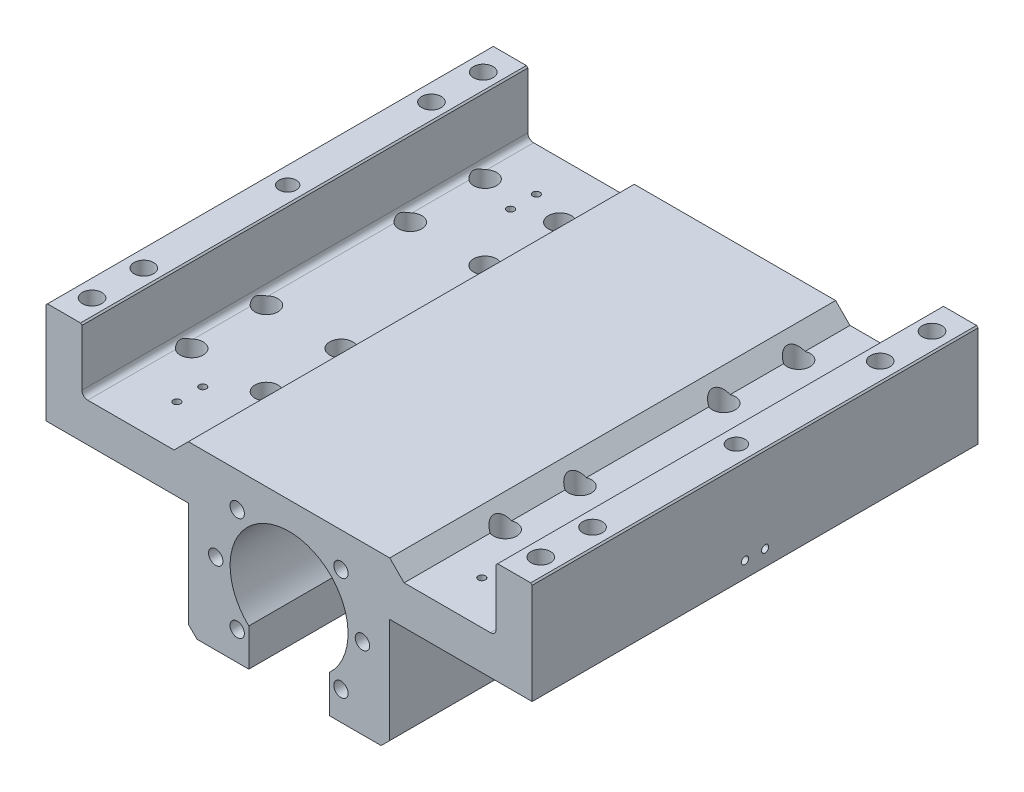
SolidWorks part; units mm, degrees
ref_plane "前视基准面" through (0, 0, 0) normal (0, 0, 1) x (1, 0, 0)
ref_plane "上视基准面" through (0, 0, 0) normal (0, 1, 0) x (1, 0, 0)
ref_plane "右视基准面" through (0, 0, 0) normal (1, 0, 0) x (0, 0, -1)
sketch "草图1" plane through (0, 0, 0) normal (0, 0, 1) x (1, 0, 0)
  line L0 (410.7552, 671.7438) -> (410.2552, 671.2438)
  line L1 (410.2552, 671.2438) -> (410.2552, 636.2438)
  line L2 (422.7552, 651.7438) -> (422.7552, 671.2438)
  line L3 (459.7552, 599.7438) -> (462.7552, 596.7438)
  line L4 (459.7552, 654.7438) -> (454.7552, 649.7438)
  line L5 (526.7552, 596.7438) -> (508.7552, 596.7438)
  line L6 (480.7552, 596.7438) -> (462.7552, 596.7438)
  line L7 (459.7552, 599.7438) -> (459.7552, 636.2438)
  line L8 (422.7552, 671.2438) -> (422.2552, 671.7438)
  line L9 (480.7552, 596.7438) -> (480.7552, 612.6506)
  line L10 (410.2552, 636.2438) -> (459.7552, 636.2438)
  line L11 (529.7552, 636.2438) -> (579.2552, 636.2438)
  line L12 (564.7552, 649.7438) -> (534.7552, 649.7438)
  line L13 (454.7552, 649.7438) -> (424.7552, 649.7438)
  line L14 (567.2552, 671.7438) -> (566.7552, 671.2438)
  line L15 (459.7552, 654.7438) -> (529.7552, 654.7438)
  line L16 (529.7552, 636.2438) -> (529.7552, 599.7438)
  line L17 (578.7552, 671.7438) -> (567.2552, 671.7438)
  line L18 (422.2552, 671.7438) -> (410.7552, 671.7438)
  line L19 (534.7552, 649.7438) -> (529.7552, 654.7438)
  line L20 (526.7552, 596.7438) -> (529.7552, 599.7438)
  line L21 (566.7552, 671.2438) -> (566.7552, 651.7438)
  line L22 (579.2552, 636.2438) -> (579.2552, 671.2438)
  line L23 (579.2552, 671.2438) -> (578.7552, 671.7438)
  line L24 (508.7552, 596.7438) -> (508.7552, 612.6506)
  arc A0 (422.7552, 651.7438) -> (424.7552, 649.7438) centre (424.7552, 651.7438) ccw
  arc A1 (564.7552, 649.7438) -> (566.7552, 651.7438) centre (564.7552, 651.7438) ccw
  arc A2 (508.7552, 612.6506) -> (480.7552, 612.6506) centre (494.7552, 624.744) ccw
extrude "凸台-拉伸1" add sketch "草图1" along normal blind 155
sketch "草图2" plane through (0, 0, 155) normal (0, 0, 1) x (1, 0, 0)
  circle A0 centre (494.7552, 624.744) radius 20.5
  dimension "D1" = 41
extrude "切除-拉伸1" cut sketch "草图2" against normal blind 100
sketch "草图3" plane through (0, 0, 155) normal (0, 0, 1) x (1, 0, 0)
  line L0 (494.7552, 624.744) -> (494.7552, 663.4123) construction
  line L1 (494.7552, 624.744) -> (440.7565, 624.744) construction
  line L3 (494.7552, 624.744) -> (464.9696, 654.5296) construction
  line L4 (494.7552, 624.744) -> (527.5427, 657.5315) construction
  circle A0 centre (494.7552, 624.744) radius 25.5 construction
  dimension "D3" = 51
  dimension "D1" = 45
  dimension "D2" = 45
hole_wizard "M6 螺纹孔1" positions "3D草图1" profile "草图4" tap size "M6" standard "Gb"
sketch3d "3D草图1"
  line L0 (494.7552, 624.744, 155) -> (464.9696, 654.5296, 155) construction
  line L1 (494.7552, 624.744, 155) -> (440.7565, 624.744, 155) construction
  line L2 (494.7552, 624.744, 155) -> (527.5427, 657.5315, 155) construction
  circle A0 centre (494.7552, 624.744, 155) radius 25.5 construction
  point P0 (476.724, 642.7752, 155)
  point P6 (494.7552, 624.744, 180.5)
  point P7 (469.2552, 624.744, 155)
  point P11 (476.724, 606.7128, 155)
  point P15 (512.7864, 606.7128, 155)
  point P17 (520.2552, 624.744, 155)
  point P19 (512.7864, 642.7752, 155)
sketch "草图4" plane through (476.724, 642.7752, 155) normal (1, 0, 0) x (0, -1, 0)
  line L0 (0, 0) -> (0, 21.5022)
  line L1 (0, 21.5022) -> (2.5, 20)
  line L2 (2.5, 20) -> (2.5, 0)
  line L5 (2.5, 0) -> (0, 0)
  line L10 (0, 21.5022) -> (-2.5, 20) construction
  line L11 (0, -6.35) -> (0, 107.95) construction
  dimension "螺纹孔钻头直径" = 5
  dimension "螺纹孔钻头深度" = 20
  dimension "导头角度" = 118
cosmetic thread "孔螺蚊线1" parameters "D1"=12, "D2"=6
cosmetic thread "孔螺蚊线2" parameters "D1"=12, "D2"=6
cosmetic thread "孔螺蚊线3" parameters "D1"=12, "D2"=6
cosmetic thread "孔螺蚊线4" parameters "D1"=12, "D2"=6
cosmetic thread "孔螺蚊线5" parameters "D1"=12, "D2"=6
cosmetic thread "孔螺蚊线6" parameters "D1"=12, "D2"=6
hole_wizard "M3 螺纹孔1" positions "草图6" profile "草图5" tap size "M3" standard "Gb"
sketch "草图6" plane through (410.2552, 0, 0) normal (-1, 0, 0) x (0, 0, 1)
  line L0 (0, 671.2438) -> (0, 636.2438) construction
  line L1 (155, 671.7438) -> (0, 671.7438) construction
  point P0 (74, 641.7438)
  point P2 (81, 641.7438)
  dimension "D1" = 7
  dimension "D2" = 74
  dimension "D3" = 30
sketch "草图5" plane through (410.2552, 641.7438, 74) normal (0, 1, 0) x (0, 0, 1)
  line L0 (0, 0) -> (0, 4.7511)
  line L1 (0, 4.7511) -> (1.25, 4)
  line L2 (1.25, 4) -> (1.25, 0)
  line L5 (1.25, 0) -> (0, 0)
  line L10 (0, 4.7511) -> (-1.25, 4) construction
  line L11 (0, -6.35) -> (0, 107.95) construction
  dimension "螺纹孔钻头直径" = 2.5
  dimension "螺纹孔钻头深度" = 4
  dimension "导头角度" = 118
cosmetic thread "孔螺蚊线7" parameters "D1"=4, "D2"=3
cosmetic thread "孔螺蚊线8" parameters "D1"=4, "D2"=3
hole_wizard "M3 螺纹孔2" positions "草图8" profile "草图7" tap size "M3" standard "Gb"
sketch "草图8" plane through (579.2552, 0, 0) normal (1, 0, 0) x (0, 0, -1)
  line L0 (0, 636.2438) -> (0, 671.2438) construction
  line L1 (-155, 671.7438) -> (0, 671.7438) construction
  point P0 (-74, 641.7438)
  point P2 (-81, 641.7438)
  dimension "D1" = 7
  dimension "D2" = 74
  dimension "D3" = 30
sketch "草图7" plane through (579.2552, 641.7438, 74) normal (0, 1, 0) x (0, 0, -1)
  line L0 (0, 0) -> (0, 8.2511)
  line L1 (0, 8.2511) -> (1.25, 7.5)
  line L2 (1.25, 7.5) -> (1.25, 0)
  line L5 (1.25, 0) -> (0, 0)
  line L10 (0, 8.2511) -> (-1.25, 7.5) construction
  line L11 (0, -6.35) -> (0, 107.95) construction
  dimension "螺纹孔钻头直径" = 2.5
  dimension "螺纹孔钻头深度" = 7.5
  dimension "导头角度" = 118
cosmetic thread "孔螺蚊线9" parameters "D1"=6, "D2"=3
cosmetic thread "孔螺蚊线10" parameters "D1"=6, "D2"=3
hole_wizard "M8 螺纹孔1" positions "草图10" profile "草图9" tap size "M8" standard "Gb"
sketch "草图10" plane through (0, 671.7438, 0) normal (0, 1, 0) x (1, 0, 0)
  line L0 (578.7552, -155) -> (567.2552, -155) construction
  line L1 (578.7552, 0) -> (567.2552, 0) construction
  line L2 (579.2552, -155) -> (579.2552, 0) construction
  point P0 (572.7552, -9.5)
  point P2 (572.7552, -27.5)
  point P4 (572.7552, -127.5)
  point P6 (572.7552, -145.5)
  point P8 (416.7552, -145.5)
  point P10 (416.7552, -127.5)
  point P12 (416.7552, -27.5)
  point P14 (416.7552, -9.5)
  dimension "D1" = 156
  dimension "D2" = 100
  dimension "D3" = 27.5
  dimension "D4" = 136
  dimension "D5" = 9.5
  dimension "D6" = 6.5
sketch "草图9" plane through (572.7552, 671.7438, 9.5) normal (1, 0, 0) x (0, 0, 1)
  line L0 (0, 0) -> (0, 22.0429)
  line L1 (0, 22.0429) -> (3.4, 20)
  line L2 (3.4, 20) -> (3.4, 0)
  line L5 (3.4, 0) -> (0, 0)
  line L10 (0, 22.0429) -> (-3.4, 20) construction
  line L11 (0, -6.35) -> (0, 107.95) construction
  dimension "螺纹孔钻头直径" = 6.8
  dimension "螺纹孔钻头深度" = 20
  dimension "导头角度" = 118
cosmetic thread "孔螺蚊线11" parameters "D1"=16, "D2"=8
cosmetic thread "孔螺蚊线12" parameters "D1"=16, "D2"=8
cosmetic thread "孔螺蚊线13" parameters "D1"=16, "D2"=8
cosmetic thread "孔螺蚊线14" parameters "D1"=16, "D2"=8
cosmetic thread "孔螺蚊线15" parameters "D1"=16, "D2"=8
cosmetic thread "孔螺蚊线16" parameters "D1"=16, "D2"=8
cosmetic thread "孔螺蚊线17" parameters "D1"=16, "D2"=8
cosmetic thread "孔螺蚊线18" parameters "D1"=16, "D2"=8
hole_wizard "M3 螺纹孔3" positions "3D草图2" profile "草图11" tap size "M3" standard "Gb"
sketch3d "3D草图2"
  line L2 (564.7552, 649.7438, 155) -> (564.7552, 649.7438, 0) construction
  line L3 (454.7552, 649.7438, 0) -> (424.7552, 649.7438, 0) construction
  line L4 (454.7552, 649.7438, 155) -> (424.7552, 649.7438, 155) construction
  point P0 (440.7552, 649.7438, 15)
  point P2 (440.7552, 649.7438, 24)
  point P4 (440.7552, 649.7438, 131)
  point P6 (440.7552, 649.7438, 140)
  point P8 (546.7552, 649.7438, 131)
  point P10 (546.7552, 649.7438, 140)
  point P12 (546.7552, 649.7438, 15)
  point P14 (546.7552, 649.7438, 24)
  dimension "D1" = 106
  dimension "D2" = 18
  dimension "D3" = 15
  dimension "D4" = 9
  dimension "D5" = 15
  dimension "D6" = 9
sketch "草图11" plane through (440.7552, 649.7438, 15) normal (1, 0, 0) x (0, 0, 1)
  line L0 (0, 0) -> (0, 8.7511)
  line L1 (0, 8.7511) -> (1.25, 8)
  line L2 (1.25, 8) -> (1.25, 0)
  line L5 (1.25, 0) -> (0, 0)
  line L10 (0, 8.7511) -> (-1.25, 8) construction
  line L11 (0, -6.35) -> (0, 107.95) construction
  dimension "螺纹孔钻头直径" = 2.5
  dimension "螺纹孔钻头深度" = 8
  dimension "导头角度" = 118
cosmetic thread "孔螺蚊线19" parameters "D1"=6, "D2"=3
cosmetic thread "孔螺蚊线20" parameters "D1"=6, "D2"=3
cosmetic thread "孔螺蚊线21" parameters "D1"=6, "D2"=3
cosmetic thread "孔螺蚊线22" parameters "D1"=6, "D2"=3
cosmetic thread "孔螺蚊线23" parameters "D1"=6, "D2"=3
cosmetic thread "孔螺蚊线24" parameters "D1"=6, "D2"=3
cosmetic thread "孔螺蚊线25" parameters "D1"=6, "D2"=3
cosmetic thread "孔螺蚊线26" parameters "D1"=6, "D2"=3
hole_wizard "打孔尺寸根据内六角圆柱头螺钉的类型3" positions "3D草图4" profile "草图15" counterbore size "M3" standard "Gb"
sketch3d "3D草图4"
  line L0 (564.7552, 649.7438, 155) -> (564.7552, 649.7438, 0) construction
  line L2 (564.7552, 649.7438, 0) -> (534.7552, 649.7438, 0) construction
  line L3 (529.7552, 654.7438, 155) -> (529.7552, 654.7438, 0) construction
  point P0 (427.2552, 654.7438, 19.3649)
  point P2 (427.2552, 654.7438, 45.3649)
  point P4 (562.2552, 654.7438, 19.3649)
  point P6 (562.2552, 654.7438, 45.3649)
  point P8 (562.2552, 654.7438, 95.3649)
  point P10 (562.2552, 654.7438, 121.3649)
  point P12 (427.2552, 654.7438, 95.3649)
  point P14 (427.2552, 654.7438, 121.3649)
  point P24 (564.7552, 649.7438, 134.0322)
  point P34 (536.2552, 654.7438, 19.3649)
  point P36 (536.2552, 654.7438, 45.3649)
  point P38 (453.2552, 654.7438, 19.3649)
  point P40 (453.2552, 654.7438, 45.3649)
  point P42 (453.2552, 654.7438, 95.3649)
  point P44 (453.2552, 654.7438, 121.3649)
  point P46 (536.2552, 654.7438, 95.3649)
  point P48 (536.2552, 654.7438, 121.3649)
  dimension "D1" = 26
  dimension "D2" = 26
  dimension "D3" = 83
  dimension "D4" = 26
  dimension "D5" = 20
  dimension "D6" = 26
  dimension "D7" = 50
  dimension "D8" = 6.5
sketch "草图15" plane through (427.2552, 654.7438, 19.3649) normal (1, 0, 0) x (0, 0, 1)
  line L0 (0, 0) -> (0, 58)
  line L1 (0, 58) -> (2, 58)
  line L3 (2, 58) -> (2, 11)
  line L4 (2, 11) -> (4, 11)
  line L5 (4, 11) -> (4, 0)
  line L7 (4, 0) -> (0, 0)
  line L11 (0, -6.35) -> (0, 107.95) construction
  dimension "通孔孔直径" = 4
  dimension "通孔孔深度" = 58
  dimension "柱形沉头孔直径" = 8
  dimension "柱形沉头孔深度" = 11
hole_wizard "Ø6.0 (6) 直径孔1" positions "草图17" profile "草图16" hole size "Ø6.0" standard "Gb"
sketch "草图17" plane through (0, 671.7438, 0) normal (0, 1, 0) x (1, 0, 0)
  line L0 (422.2552, 0) -> (410.7552, 0) construction
  line L1 (579.2552, -155) -> (579.2552, 0) construction
  point P0 (416.7552, -77.5)
  point P2 (572.7552, -77.5)
  point P5 (416.5052, 0)
  dimension "D1" = 156
  dimension "D2" = 77.5
  dimension "D3" = 6.5
sketch "草图16" plane through (416.7552, 671.7438, 77.5) normal (1, 0, 0) x (0, 0, 1)
  line L0 (0, 0) -> (0, 7.8026)
  line L1 (0, 7.8026) -> (3, 6)
  line L2 (3, 6) -> (3, 0)
  line L5 (3, 0) -> (0, 0)
  line L10 (0, 7.8026) -> (-3, 6) construction
  line L11 (0, -6.35) -> (0, 107.95) construction
  dimension "孔直径" = 6
  dimension "孔深度" = 6
  dimension "导头角度" = 118
